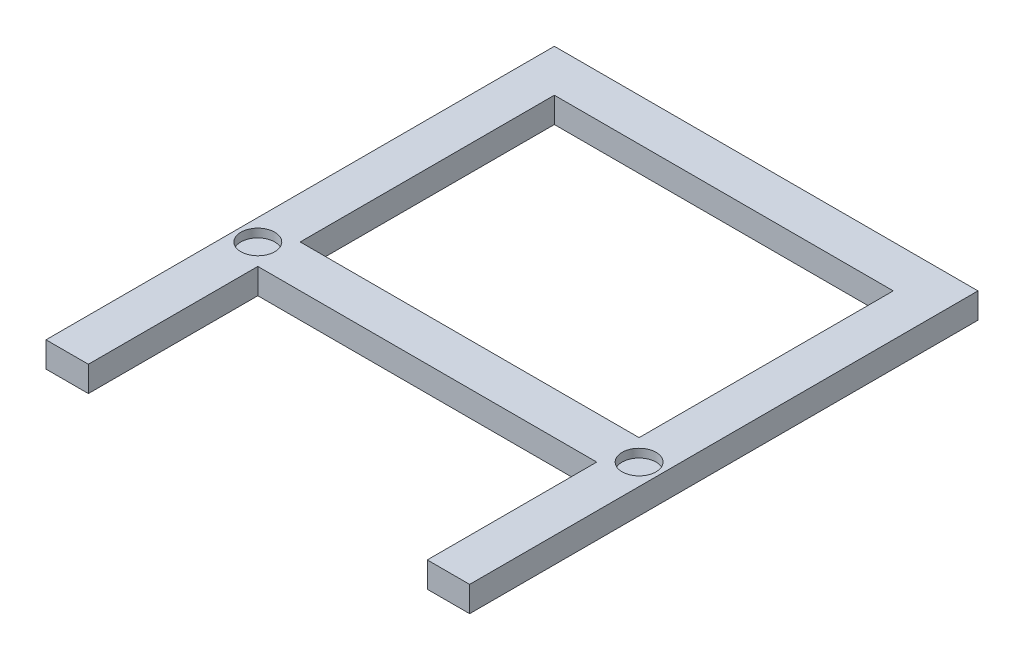
SolidWorks part; units mm, degrees
ref_plane "Front Plane" through (0, 0, 0) normal (0, 0, 1) x (1, 0, 0)
ref_plane "Top Plane" through (0, 0, 0) normal (0, 1, 0) x (1, 0, 0)
ref_plane "Right Plane" through (0, 0, 0) normal (1, 0, 0) x (0, 0, -1)
sketch "Sketch1" plane through (0, 0, 0) normal (0, 1, 0) x (1, 0, 0)
  line L0 (-50, 0) -> (50, 0)
  line L13 (50, 0) -> (50, -120)
  line L14 (50, -120) -> (40, -120)
  line L15 (40, -120) -> (40, -80)
  line L16 (40, -10) -> (-40, -10)
  line L19 (-50, -120) -> (-50, 0)
  line L23 (-50, -120) -> (-40, -120)
  line L24 (-40, -10) -> (-40, -70)
  line L25 (-40, -70) -> (40, -70)
  line L27 (40, -80) -> (-40, -80)
  line L28 (-40, -80) -> (-40, -120)
  line L29 (40, -70) -> (40, -10)
  point P3 (0, 0)
  point P13 (0, -10)
  dimension "D1" = 120
  dimension "D2" = 120
  dimension "D3" = 10
  dimension "D4" = 110
  dimension "D5" = 100
  dimension "D6" = 50
  dimension "D7" = 80
  dimension "D8" = 60
extrude "Boss-Extrude1" add sketch "Sketch1" along normal mid plane 6
sketch "Sketch2" plane through (0, 3, 0) normal (0, 1, 0) x (1, 0, 0)
  line L0 (-50, 0) -> (-50, -120) construction
  line L1 (50, -120) -> (50, 0) construction
  circle A0 centre (-45, -75) radius 4
  circle A1 centre (45, -75) radius 4
  dimension "D1" = 8
  dimension "D2" = 8
  dimension "D4" = 5
  dimension "D5" = 5
extrude "Cut-Extrude1" cut sketch "Sketch2" against normal blind 2
